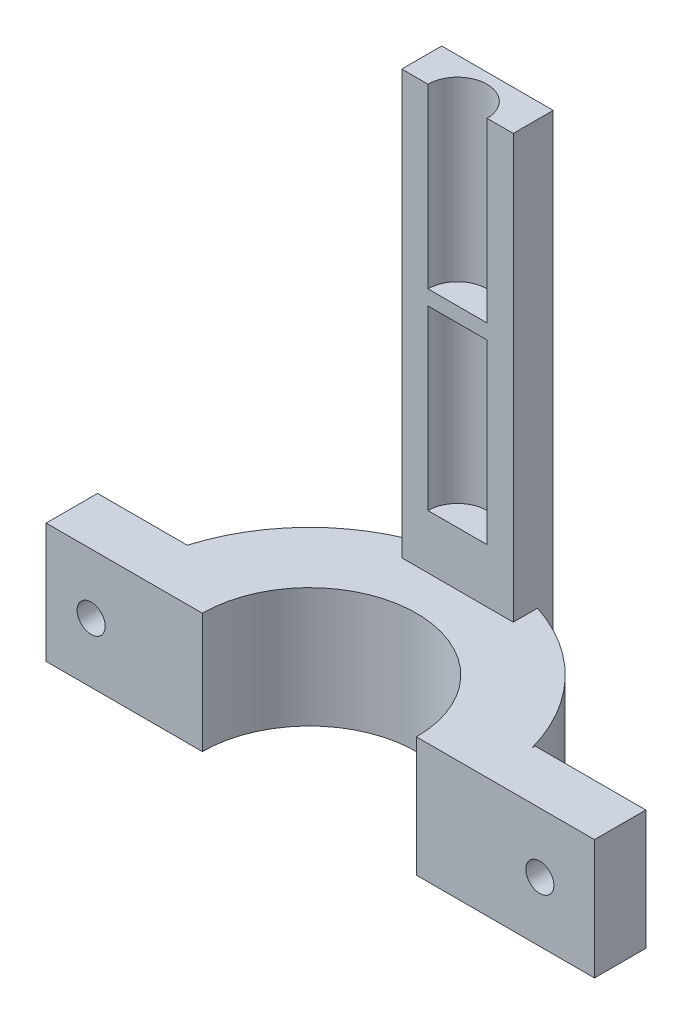
SolidWorks part; units mm, degrees
ref_plane "前基準面" through (0, 0, 0) normal (0, 0, 1) x (1, 0, 0)
ref_plane "上基準面" through (0, 0, 0) normal (0, 1, 0) x (1, 0, 0)
ref_plane "右基準面" through (0, 0, 0) normal (1, 0, 0) x (0, 0, -1)
sketch "草圖1" plane through (0, 0, 0) normal (0, 1, 0) x (1, 0, 0)
  line L1 (-14.255, 7) -> (14.255, 7)
  line L2 (-14.255, 7) -> (-14.255, -7)
  line L3 (-14.255, -7) -> (14.255, -7)
  line L4 (14.255, 7) -> (14.255, -7)
  line L5 (-14.255, 7) -> (14.255, -7) construction
  line L6 (-14.255, -7) -> (14.255, 7) construction
  point P0 (0, 0)
  dimension "D1" = 14
  dimension "D2" = 28.51
extrude "伸長-薄件1" add sketch "草圖1" along normal blind 12.25 thin thin type one direction wall 10
sketch "草圖2" plane through (0, 12.25, 0) normal (0, 1, 0) x (1, 0, 0)
  line L0 (-1014.255, 0) -> (48985.745, 0) construction
  line L1 (-14.255, 7) -> (-14.255, -7) construction
  line L2 (-19.255, -988.4004) -> (-19.255, 49011.5996) construction
  line L3 (-24.255, 17) -> (-19.255, 17) construction
  line L4 (-24.255, 17) -> (-24.255, 11.5996) construction
  line L5 (-24.255, 11.5996) -> (-19.255, 11.5996) construction
  line L6 (-19.255, 17) -> (-19.255, 11.5996) construction
  line L7 (24.255, 17) -> (19.255, 17) construction
  line L8 (24.255, 17) -> (24.255, 12.4477) construction
  line L9 (24.255, 12.4477) -> (19.255, 12.4477) construction
  line L10 (19.255, 17) -> (19.255, 12.4477) construction
  line L11 (19.255, -987.5523) -> (19.255, 49012.4477) construction
  circle A0 centre (-19.255, 0) radius 1.91
  circle A1 centre (19.255, 0) radius 1.91
  point P5 (-14.255, 0)
  dimension "D3" = 3.82
  dimension "D4" = 3.82
  dimension "D1" = 5
  dimension "D2" = 5
extrude "除料-伸長1" cut sketch "草圖2" against normal through all
sketch "草圖4" plane through (0, 0, 0) normal (0, -1, 0) x (1, 0, 0)
  line L0 (-1000, 0) -> (49000, 0) construction
  line L1 (24.255, 17) -> (24.255, -17) construction
  line L2 (11.255, 6.955) -> (24.255, 6.955)
  line L3 (11.255, 6.955) -> (11.255, -6.955)
  line L4 (11.255, -6.955) -> (24.255, -6.955)
  line L5 (24.255, 6.955) -> (24.255, -6.955)
  line L6 (11.255, 6.955) -> (24.255, -6.955) construction
  line L7 (11.255, -6.955) -> (24.255, 6.955) construction
  point P1 (17.755, 0)
  dimension "D1" = 13.91
  dimension "D2" = 13
extrude "填料-伸長1" add sketch "草圖4" along normal blind 74.82
sketch "草圖5" plane through (11.255, 0, 0) normal (-1, 0, 0) x (0, 0, 1)
  line L0 (6.955, -74.82) -> (6.955, 0) construction
  line L1 (-6.955, -74.82) -> (6.955, -74.82)
  line L2 (-6.955, -74.82) -> (-6.955, -58.59)
  line L3 (-6.955, -58.59) -> (6.955, -58.59)
  line L4 (6.955, -74.82) -> (6.955, -58.59)
  dimension "D1" = 16.23
extrude "填料-伸長2" add sketch "草圖5" along normal blind 15
sketch "草圖7" plane through (3.6267, -74.82, 0) normal (0, -1, 0) x (1, 0, 0)
  circle A0 centre (-30.9782, 0) radius 14.5
  dimension "D1" = 29
extrude "伸長-薄件2" add sketch "草圖7" against normal blind 16.23 thin
ref_plane "平面1" through (-60, 0, 0) normal (1, 0, 0) x (0, 0, -1)
sketch "草圖12" plane through (0, 0, -6.955) normal (0, 0, -1) x (-1, 0, 0)
  line L0 (-996.255, -66.705) -> (49003.745, -66.705) construction
  line L1 (3.745, -74.82) -> (3.745, -58.59) construction
  line L2 (-3.755, -1058.59) -> (-3.755, 48941.41) construction
  line L3 (3.745, -58.59) -> (-11.255, -58.59) construction
  circle A0 centre (-3.8567, -66.705) radius 1.9
  point P5 (3.745, -66.705)
  point P10 (-3.755, -58.59)
  dimension "D1" = 3.8
extrude "除料-伸長4" cut sketch "草圖12" against normal through all
ref_plane "平面2" through (-55, 0, 0) normal (1, 0, 0) x (0, 0, -1)
sketch "草圖13" plane through (-55, 0, 0) normal (1, 0, 0) x (0, 0, -1)
  line L1 (6.955, -58.59) -> (-6.955, -58.59)
  line L2 (6.955, -58.59) -> (6.955, -74.82)
  line L3 (6.955, -74.82) -> (-6.955, -74.82)
  line L4 (-6.955, -58.59) -> (-6.955, -74.82)
extrude "填料-伸長3" add sketch "草圖13" along normal blind 10 and the other way blind 8
sketch "草圖14" plane through (0, 0, -6.955) normal (0, 0, -1) x (-1, 0, 0)
  line L0 (-949.1564, -66.705) -> (49050.8436, -66.705) construction
  line L1 (50.8436, -58.59) -> (50.8436, -74.82) construction
  line L2 (56.9218, -1058.59) -> (56.9218, 48941.41) construction
  line L3 (63, -58.59) -> (50.8436, -58.59) construction
  circle A0 centre (56.908, -66.705) radius 1.9
  point P5 (50.8436, -66.705)
  point P10 (56.9218, -58.59)
  dimension "D1" = 3.8
extrude "除料-伸長5" cut sketch "草圖14" against normal through all
sketch "草圖16" plane through (0, 12.25, 0) normal (0, 1, 0) x (1, 0, 0)
  line L0 (-63, 6.955) -> (-63, -6.955) construction
  line L1 (-63, 0) -> (27.7094, 0)
  line L2 (-63, 0) -> (-63, -28.9551)
  line L3 (-63, -28.9551) -> (27.7094, -28.9551)
  line L4 (27.7094, 0) -> (27.7094, -28.9551)
extrude "除料-伸長7" cut sketch "草圖16" against normal through all
sketch "草圖17" plane through (11.255, 0, 0) normal (-1, 0, 0) x (0, 0, 1)
  line L1 (0, -58.59) -> (-20.2305, -58.59)
  line L2 (0, -58.59) -> (0, 22.1336)
  line L3 (0, 22.1336) -> (-20.2305, 22.1336)
  line L4 (-20.2305, -58.59) -> (-20.2305, 22.1336)
sketch "草圖18" plane through (0, 0, 0) normal (0, 0, 1) x (1, 0, 0)
  line L0 (11.255, -58.59) -> (11.255, 22.1336) construction
  line L1 (24.255, -74.82) -> (11.255, -74.82)
  line L2 (24.255, -74.82) -> (24.255, 18.2609)
  line L3 (24.255, 18.2609) -> (11.255, 18.2609)
  line L4 (11.255, -74.82) -> (11.255, 18.2609)
extrude "除料-伸長10" cut sketch "草圖18" against normal blind 27
extrude "除料-伸長11" cut sketch "草圖17" against normal blind 27 and the other way blind 57
ref_plane "平面3" through (0, 0, -30) normal (0, 0, 1) x (1, 0, 0)
sketch "草圖21" plane through (0, 0, -30) normal (0, 0, 1) x (1, 0, 0)
  line L0 (-27.2943, -1058.59) -> (-27.2943, 48941.41) construction
  line L1 (-3.745, -58.59) -> (-50.8436, -58.59) construction
  line L2 (-3.745, -58.59) -> (-3.745, -74.82) construction
  line L3 (-19.745, -27.2694) -> (-34.8436, -27.2694)
  line L4 (-19.745, -27.2694) -> (-19.745, -69.7694)
  line L5 (-19.745, -69.7694) -> (-34.8436, -69.7694)
  line L6 (-34.8436, -27.2694) -> (-34.8436, -69.7694)
  line L7 (-50.8436, -58.59) -> (-50.8436, -74.82) construction
  point P5 (-27.2943, -58.59)
  dimension "D1" = 16
  dimension "D2" = 16
  dimension "D3" = 42.5
extrude "填料-伸長6" add sketch "草圖21" along normal blind 10
sketch "草圖22" plane through (0, -27.2694, 0) normal (0, 1, 0) x (1, 0, 0)
  line L0 (-34.8436, 20) -> (-19.745, 20) construction
  circle A0 centre (-27.2943, 20) radius 4.005
  dimension "D1" = 8.01
extrude "除料-伸長12" cut sketch "草圖22" against normal blind 24
sketch "草圖23" plane through (0, -27.2694, 0) normal (0, 1, 0) x (1, 0, 0)
  line L0 (-19.745, 20) -> (-19.745, 30) construction
  line L1 (-34.8436, 30) -> (-19.745, 30)
  line L2 (-34.8436, 30) -> (-34.8436, 25.4125)
  line L3 (-34.8436, 25.4125) -> (-19.745, 25.4125)
  line L4 (-19.745, 30) -> (-19.745, 25.4125)
extrude "除料-伸長13" cut sketch "草圖23" against normal through all
sketch "草圖24" plane through (0, -27.2694, 0) normal (0, 1, 0) x (1, 0, 0)
  line L1 (-34.8436, 25.4125) -> (-19.745, 25.4125)
  line L2 (-34.8436, 25.4125) -> (-34.8436, 20)
  line L3 (-34.8436, 20) -> (-19.745, 20)
  line L4 (-19.745, 25.4125) -> (-19.745, 20)
extrude "填料-伸長8" add sketch "草圖24" along normal blind 26
sketch "草圖25" plane through (0, -1.2694, 0) normal (0, 1, 0) x (1, 0, 0)
  line L0 (-34.8436, 20) -> (-19.745, 20) construction
  circle A0 centre (-27.2943, 20) radius 4.005
  dimension "D1" = 8.01
extrude "除料-伸長14" cut sketch "草圖25" against normal blind 24
